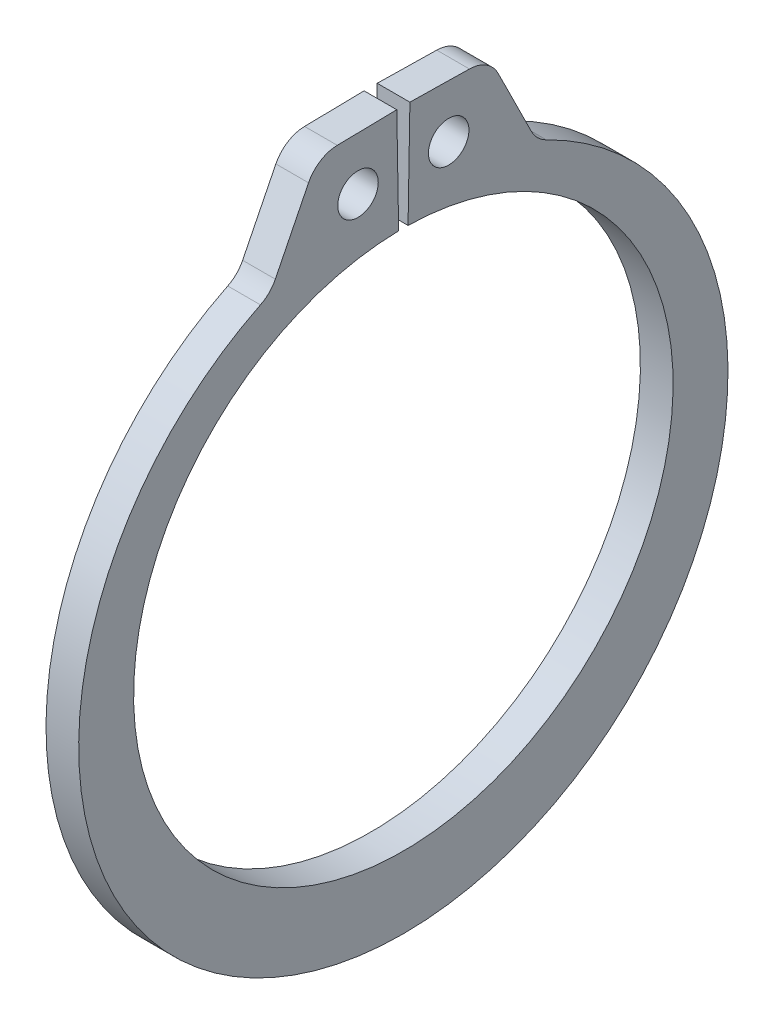
SolidWorks part; units mm, degrees
material "Cast Carbon Steel"
ref_plane "Front" through (0, 0, 0) normal (0, 0, 1) x (1, 0, 0)
ref_plane "Top" through (0, 0, 0) normal (0, 1, 0) x (1, 0, 0)
ref_plane "Right" through (0, 0, 0) normal (1, 0, 0) x (0, 0, -1)
sketch "Sketch1" plane through (0, 0, 0) normal (1, 0, 0) x (0, 0, -1)
  line L0 (0, 0) -> (0, 8.8011) construction
  line L1 (-0.1536, 8.7998) -> (-0.2139, 12.2536)
  line L2 (0.2139, 12.2536) -> (2.8043, 12.2084)
  line L3 (2.8043, 12.2084) -> (4.342, 9.1152)
  line L4 (0.1536, 8.7998) -> (0.2139, 12.2536)
  line L5 (-0.2139, 12.2536) -> (-2.8043, 12.2084)
  line L6 (-2.8043, 12.2084) -> (-4.342, 9.1152)
  line L7 (-4.342, 9.1152) -> (-3.7849, 7.9457) construction
  line L8 (4.342, 9.1152) -> (3.7849, 7.9457) construction
  line L9 (0, -8.8011) -> (0, -11.1379) construction
  line L10 (-2.8043, 12.2084) -> (-0.1536, 8.7998) construction
  line L11 (0, 8.8011) -> (0, 12.2555) construction
  line L12 (-8.8011, 0) -> (8.8011, 0) construction
  circle A0 centre (0, 0) radius 8.8011 construction
  arc A1 (-0.1536, 8.7998) -> (0.1536, 8.7998) centre (0, 0) ccw
  circle A3 centre (0, 0) radius 13.589 construction
  circle A4 centre (-1.4789, 10.5041) radius 0.6604
  circle A5 centre (1.4789, 10.5041) radius 0.6604
  arc A6 (-4.342, 9.1152) -> (4.342, 9.1152) centre (0, -0.5459) ccw
  point P0 (0, -11.1379)
  dimension "A" = 17.6022
  dimension "Hole" = 1.3208
  dimension "Smin" = 1.2954
  dimension "H" = 3.4544
  dimension "D2" = 2.5908
  dimension "Angle" = 1
extrude "Extrude1" add sketch "Sketch1" along normal mid plane 1.0668
fillet "Fillet1" radius 1.0668 4 edges at (0, 9.1152, 4.342) (0, 9.1152, -4.342) (0, 12.2084, 2.8043) (0, 12.2084, -2.8043)
sketch "Sketch2" plane through (0, 0, 0) normal (0, 0, 1) x (1, 0, 0)
  line L0 (-5.9182, 0) -> (15.4178, 0)
  line L1 (15.4178, 0) -> (15.4178, -9.525)
  line L2 (-5.9182, 0) -> (-5.9182, -8.9408)
  line L3 (15.4178, -9.525) -> (0.5842, -9.525)
  line L4 (0.5842, -9.525) -> (0.5842, -8.9408)
  line L5 (0.5842, -8.9408) -> (-0.5842, -8.9408)
  line L6 (-0.5842, -8.9408) -> (-0.5842, -9.525)
  line L7 (-0.5842, -9.525) -> (-5.9182, -9.525) construction
  line L8 (-5.9182, -9.525) -> (-5.9182, 0) construction
  line L9 (15.4178, 0) -> (76.391, 0) construction
  line L10 (-5.9182, -8.9408) -> (-5.334, -9.525)
  line L11 (-5.334, -9.525) -> (-0.5842, -9.525)
  point P10 (0, -8.9408)
  dimension "D2" = 21.336
  dimension "D3" = 5.334
  dimension "D1" = 45
revolve "Revolve1" [suppressed] add sketch "Sketch2" angle 360 about L9
delete or keep bodies "Body-Delete1" [suppressed] type delete bodies bodies 122
equation "\"D2@Sketch2\" = \"D1@Extrude1\"*20"
equation "\"D3@Sketch2\" = \"D2@Sketch2\"/4"
equation "\"D2@Sketch1\" = \"H@Sketch1\"*.75"
equation "\"D1@Fillet1\" = \"D1@Extrude1\""
